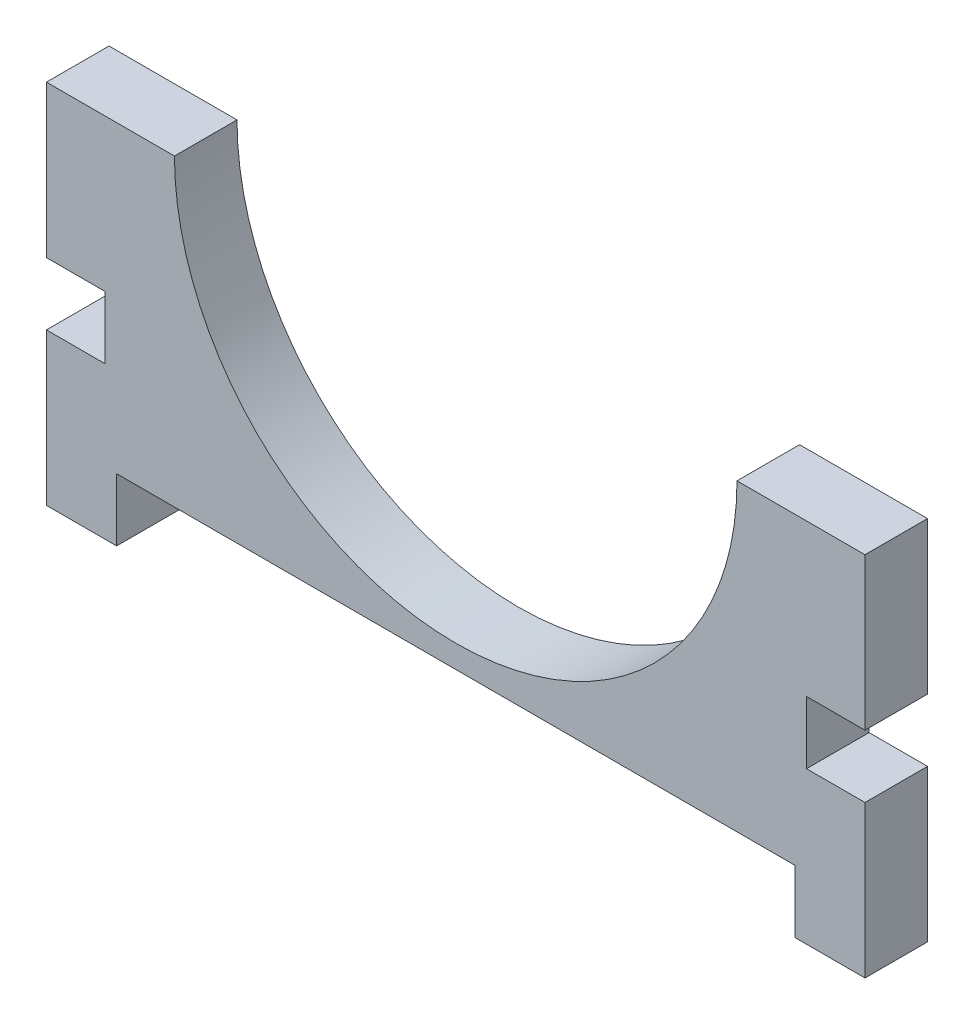
SolidWorks part; units mm, degrees
ref_plane "Front Plane" through (0, 0, 0) normal (0, 0, 1) x (1, 0, 0)
ref_plane "Top Plane" through (0, 0, 0) normal (0, 1, 0) x (1, 0, 0)
ref_plane "Right Plane" through (0, 0, 0) normal (1, 0, 0) x (0, 0, -1)
sketch "Model" plane through (0, 0, 0) normal (0, 0, 1) x (1, 0, 0)
  line L0 (59.055, 31.35) -> (70, 31.35)
  line L1 (70, 31.35) -> (70, 18.35)
  line L2 (70, 18.35) -> (65, 18.35)
  line L3 (65, 18.35) -> (65, 13)
  line L4 (65, 13) -> (70, 13)
  line L5 (70, 13) -> (70, 0)
  line L6 (70, 0) -> (64, 0)
  line L7 (64, 0) -> (64, 5.35)
  line L8 (6, 5.35) -> (64, 5.35)
  line L9 (6, 0) -> (6, 5.35)
  line L10 (0, 0) -> (6, 0)
  line L11 (0, 13) -> (0, 0)
  line L12 (5, 13) -> (0, 13)
  line L13 (5, 18.35) -> (5, 13)
  line L14 (0, 18.35) -> (5, 18.35)
  line L15 (0, 31.35) -> (0, 18.35)
  line L16 (10.945, 31.35) -> (0, 31.35)
  line L17 (35, 31.35) -> (35, -8.3305) construction
  arc A0 (10.945, 31.35) -> (59.055, 31.35) centre (35, 31.35) ccw
  point P19 (35, 5.35)
  dimension "D7" = 24.055
  dimension "D1" = 6
  dimension "D2" = 5.35
  dimension "D3" = 5.35
  dimension "D4" = 13
  dimension "D5" = 31.35
  dimension "D6" = 5
  dimension "D8" = 10.945
  dimension "D9" = 70
  dimension "D10" = 1.945
extrude "Boss-Extrude1" add sketch "Model" along normal blind 5.35
